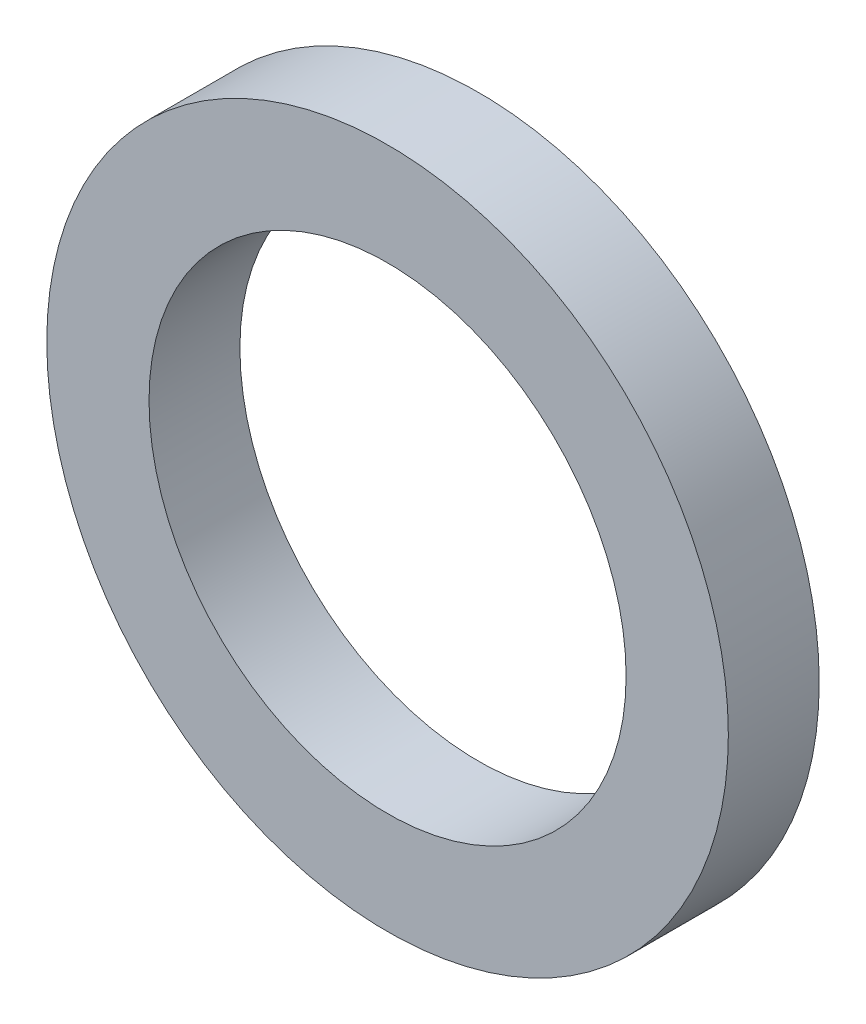
SolidWorks part; units mm, degrees
material "PTFE (general)"
ref_plane "Front Plane" through (0, 0, 0) normal (0, 0, 1) x (1, 0, 0)
ref_plane "Top Plane" through (0, 0, 0) normal (0, 1, 0) x (1, 0, 0)
ref_plane "Right Plane" through (0, 0, 0) normal (1, 0, 0) x (0, 0, -1)
sketch "Sketch1" plane through (0, 0, 0) normal (0, 0, 1) x (1, 0, 0)
  circle A0 centre (0, 0) radius 5.25
  circle A1 centre (0, 0) radius 7.5
  dimension "D1" = 15
  dimension "D2" = 10.5
extrude "Extrude1" add sketch "Sketch1" along normal blind 2
